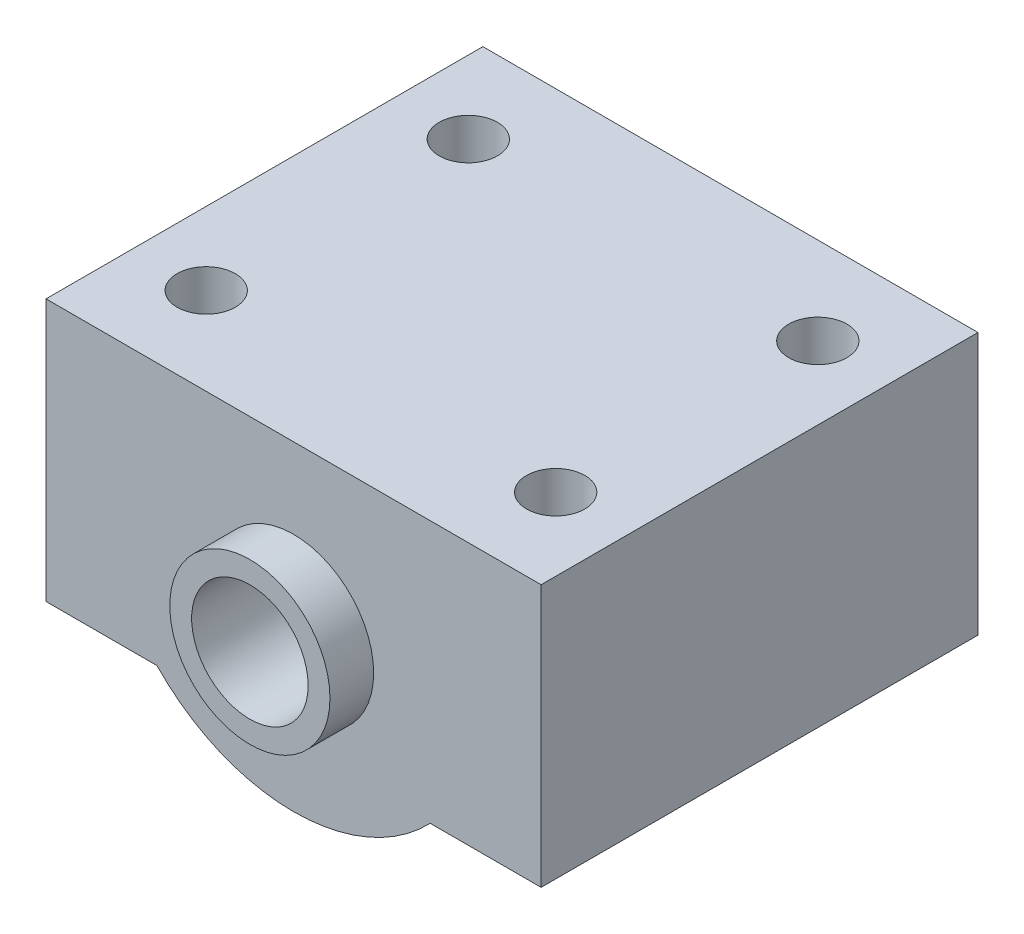
SolidWorks part; units mm, degrees
ref_plane "Front Plane" through (0, 0, 0) normal (0, 0, 1) x (1, 0, 0)
ref_plane "Top Plane" through (0, 0, 0) normal (0, 1, 0) x (1, 0, 0)
ref_plane "Right Plane" through (0, 0, 0) normal (1, 0, 0) x (0, 0, -1)
sketch "Sketch1" plane through (0, 0, 0) normal (0, 0, 1) x (1, 0, 0)
  line L0 (-9.3808, -9) -> (-17, -9)
  line L1 (17, -9) -> (9.3808, -9)
  line L2 (17, -9) -> (17, 9)
  line L3 (17, 9) -> (-17, 9)
  line L4 (-17, -9) -> (-17, 9)
  line L5 (17, -9) -> (-17, 9) construction
  line L6 (17, 9) -> (-17, -9) construction
  arc A0 (-9.3808, -9) -> (9.3808, -9) centre (0, 0) ccw
  point P0 (0, 0)
  dimension "D1" = 34
  dimension "D2" = 18
  dimension "D3" = 22
extrude "Boss-Extrude1" add sketch "Sketch1" along normal blind 30
sketch "Sketch5" plane through (0, 0, 30) normal (0, 0, 1) x (1, 0, 0)
  line L0 (17, 9) -> (-17, 9) construction
  circle A0 centre (0, -2) radius 4
  dimension "D1" = 8
  dimension "D2" = 11
  dimension "D3" = 17
extrude "Cut-Extrude1" cut sketch "Sketch5" against normal up to next
sketch "Sketch6" plane through (0, 0, 30) normal (0, 0, 1) x (1, 0, 0)
  circle A0 centre (0, -2) radius 4 construction
  circle A1 centre (0, -2) radius 4
  circle A2 centre (0, -2) radius 5.5
  dimension "D1" = 11
extrude "Boss-Extrude2" add sketch "Sketch6" along normal blind 3
sketch "Sketch7" plane through (0, 0, 0) normal (0, 0, -1) x (-1, 0, 0)
  circle A0 centre (0, -2) radius 4 construction
  circle A1 centre (0, -2) radius 4
  circle A2 centre (0, -2) radius 5.5
  dimension "D1" = 11
extrude "Boss-Extrude3" add sketch "Sketch7" along normal blind 3
sketch "Sketch8" plane through (0, 9, 0) normal (0, 1, 0) x (1, 0, 0)
  line L0 (0, 0) -> (0, -30) construction
  line L1 (-5.5, -30) -> (5.5, -30) construction
  line L2 (-17, -15) -> (17, -15) construction
  line L3 (-17, -30) -> (-17, 0) construction
  line L4 (17, -30) -> (17, 0) construction
  circle A0 centre (-12, -6) radius 2
  circle A2 centre (-12, -24) radius 2
  circle A3 centre (12, -24) radius 2
  circle A4 centre (12, -6) radius 2
  dimension "D2" = 4
  dimension "D1" = 18
  dimension "D3" = 5
extrude "Cut-Extrude2" cut sketch "Sketch8" against normal blind 6
sketch "Sketch9" plane through (0, -9, 0) normal (0, -1, 0) x (1, 0, 0)
  line L0 (-17, 15) -> (17, 15) construction
  line L1 (-17, 30) -> (-17, 0) construction
  line L2 (17, 30) -> (17, 0) construction
  line L3 (0, 0) -> (0, 30) construction
  line L4 (9.3808, 30) -> (-9.3808, 30) construction
  circle A0 centre (-12, 27) radius 1.7
  circle A1 centre (-12, 3) radius 1.7
  circle A2 centre (12, 3) radius 1.7
  circle A3 centre (12, 27) radius 1.7
  dimension "D2" = 3.4
  dimension "D1" = 24
  dimension "D3" = 5
extrude "Cut-Extrude3" cut sketch "Sketch9" against normal blind 10
